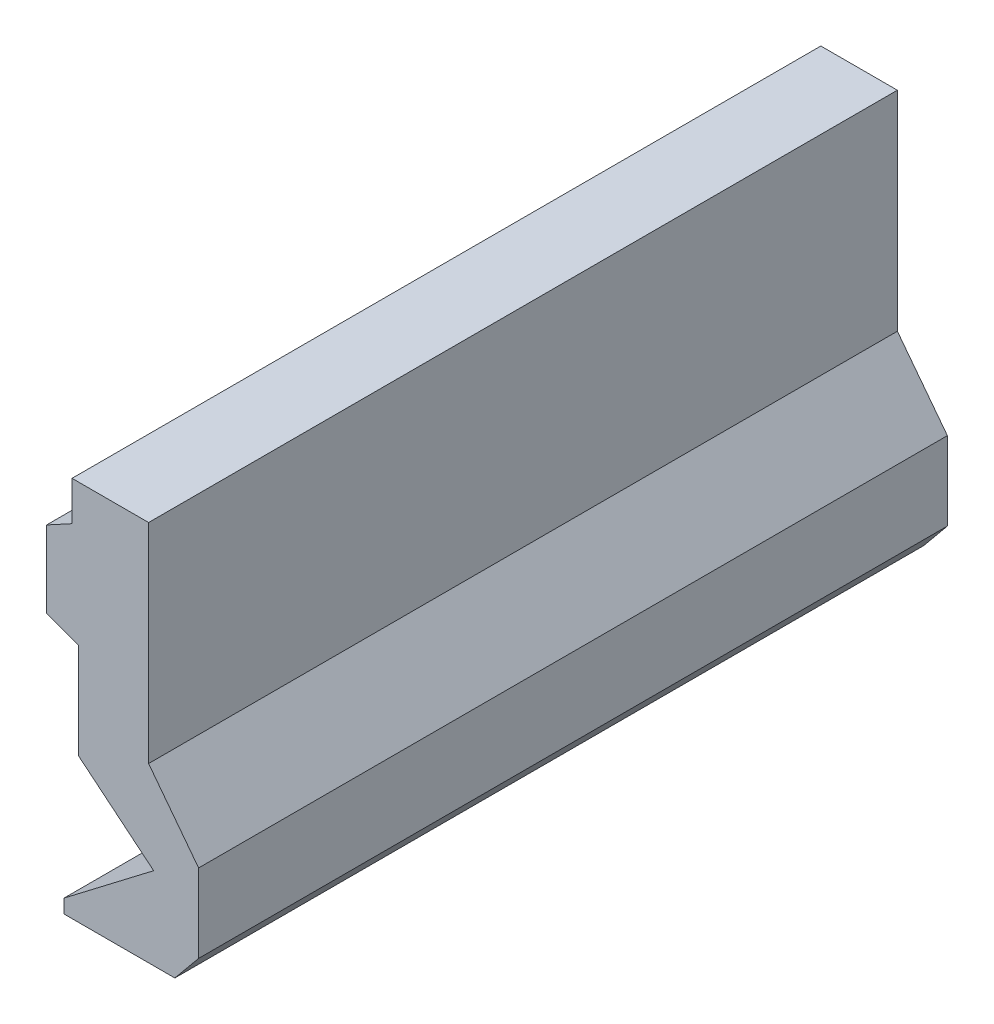
SolidWorks part; units mm, degrees
ref_plane "정면" through (0, 0, 0) normal (0, 0, 1) x (1, 0, 0)
ref_plane "윗면" through (0, 0, 0) normal (0, 1, 0) x (1, 0, 0)
ref_plane "우측면" through (0, 0, 0) normal (1, 0, 0) x (0, 0, -1)
sketch "스케치2" plane through (0, 0, 0) normal (0, 0, 1) x (1, 0, 0)
  line L0 (0.1611, -2.1275) -> (0.1611, -5.1993)
  line L1 (1.4396, -9.5002) -> (4.4503, -11.9801)
  line L2 (4.4503, -11.9801) -> (0.86, -14.7248)
  line L3 (0.86, -14.7248) -> (0.86, -15.2788)
  line L4 (0.86, -15.2788) -> (5.2985, -15.2788)
  line L5 (5.2985, -15.2788) -> (6.2508, -14.1227)
  line L6 (6.2508, -14.1227) -> (6.2508, -10.984)
  line L7 (6.2508, -10.984) -> (4.2473, -8.3633)
  line L8 (4.2473, -8.3633) -> (4.2473, 0)
  line L9 (4.2473, 0) -> (1.1801, 0)
  line L10 (0.1611, -5.1993) -> (1.4396, -5.6694)
  line L11 (1.4396, -5.6694) -> (1.4396, -9.5002)
  line L12 (1.1801, 0) -> (1.1801, -1.5742)
  line L13 (1.1801, -1.5742) -> (0.1611, -2.1275)
  line L14 (0, 0) -> (1.1801, 0) construction
extrude "보스-돌출1" add sketch "스케치2" along normal blind 30
